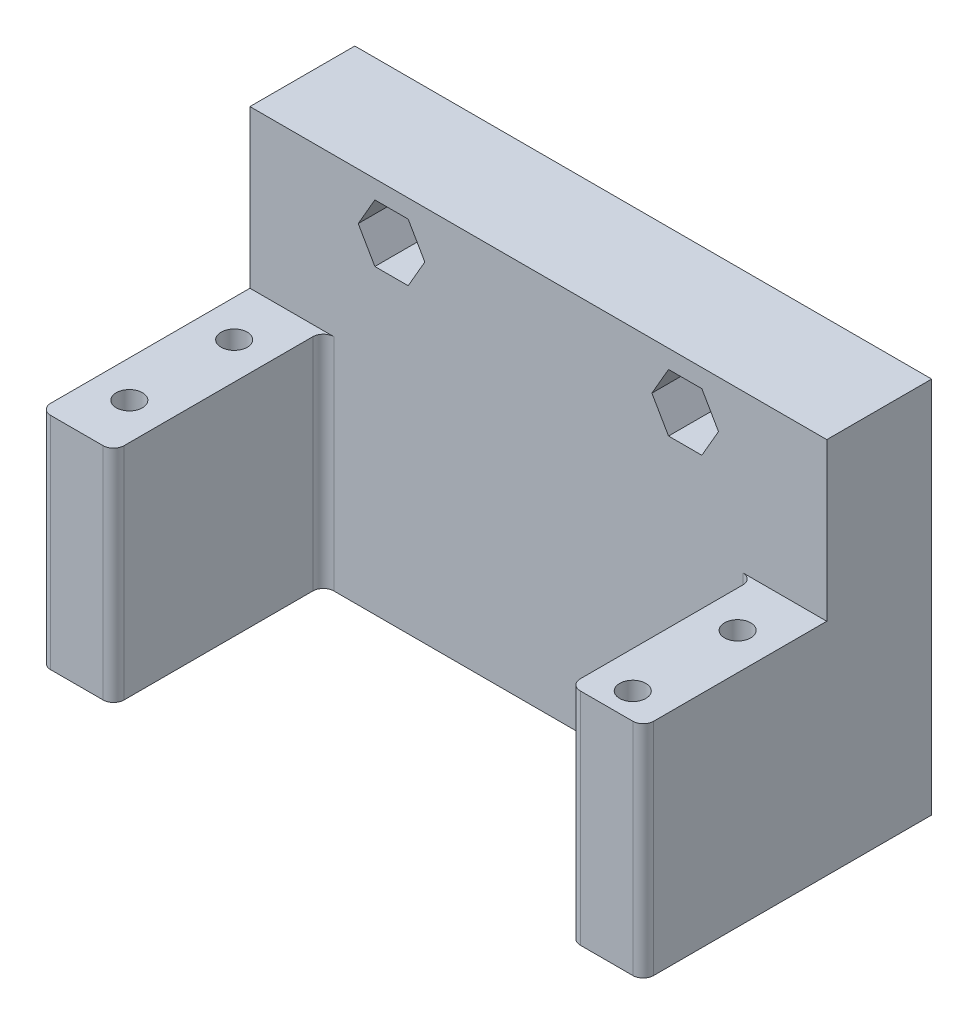
SolidWorks part; units mm, degrees
ref_plane "Front Plane" through (0, 0, 0) normal (0, 0, 1) x (1, 0, 0)
ref_plane "Top Plane" through (0, 0, 0) normal (0, 1, 0) x (1, 0, 0)
ref_plane "Right Plane" through (0, 0, 0) normal (1, 0, 0) x (0, 0, -1)
sketch "Sketch1" plane through (0, 0, 0) normal (0, 0, 1) x (1, 0, 0)
  line L1 (0, 0) -> (55, 0)
  line L2 (0, 0) -> (0, -36)
  line L3 (0, -36) -> (55, -36)
  line L4 (55, 0) -> (55, -36)
  circle A0 centre (13.5, -4.5) radius 2
  circle A1 centre (41.5, -4.5) radius 2
  dimension "D3" = 4.5
  dimension "D1" = 55
  dimension "D2" = 36
  dimension "D4" = 13.5
  dimension "D6" = 28
  dimension "D5" = 2
extrude "Boss-Extrude1" add sketch "Sketch1" along normal blind 10
sketch "Sketch2" plane through (0, -36, 0) normal (0, -1, 0) x (1, 0, 0)
  line L1 (0, 10) -> (7, 10)
  line L2 (0, 10) -> (0, 30)
  line L3 (0, 30) -> (7, 30)
  line L4 (7, 10) -> (7, 30)
  line L5 (55, 10) -> (48, 10)
  line L6 (55, 10) -> (55, 27.5)
  line L7 (55, 27.5) -> (48, 27.5)
  line L8 (48, 10) -> (48, 27.5)
  dimension "D1" = 41
  dimension "D2" = 7
  dimension "D3" = 20
extrude "Boss-Extrude2" add sketch "Sketch2" against normal blind 21
sketch "Sketch3" plane through (0, -15, 0) normal (0, 1, 0) x (1, 0, 0)
  line L0 (55, -10) -> (0, -10) construction
  line L1 (0, -30) -> (0, -10) construction
  circle A0 centre (3.5, -15) radius 1.25
  circle A1 centre (51.5, -15) radius 1.25
  circle A2 centre (51.5, -25) radius 1.25
  circle A3 centre (3.5, -25) radius 1.25
  dimension "D1" = 2
  dimension "D3" = 5
  dimension "D4" = 3.5
  dimension "D2" = 2
extrude "Cut-Extrude1" cut sketch "Sketch3" against normal blind 10
sketch "Sketch4" plane through (0, 0, 10) normal (0, 0, 1) x (1, 0, 0)
  line L1 (11.9123, -1.75) -> (10.3246, -4.5)
  line L2 (10.3246, -4.5) -> (11.9123, -7.25)
  line L3 (11.9123, -7.25) -> (15.0877, -7.25)
  line L4 (15.0877, -7.25) -> (16.6754, -4.5)
  line L5 (16.6754, -4.5) -> (15.0877, -1.75)
  line L6 (15.0877, -1.75) -> (11.9123, -1.75)
  circle A0 centre (13.5, -4.5) radius 2.75 construction
extrude "Cut-Extrude2" cut sketch "Sketch4" against normal blind 5.5
pattern_linear "LPattern1" count 2 spacing 28 along (1, 0, 0) of "Cut-Extrude2"
fillet "Fillet1" radius 1 6 edges at (48, -25.5, 27.5) (55, -25.5, 27.5) (7, -25.5, 30) (0, -25.5, 30) (48, -25.5, 10) (7, -25.5, 10)
sketch "Sketch5" plane through (0, 0, 0) normal (0, 1, 0) x (1, 0, 0)
  line L0 (27.5, 0) -> (27.5, -20)
  line L1 (55, 0) -> (0, 0) construction
  line L2 (27.5, -20) -> (37.5, -20)
  line L3 (27.5, 0) -> (27.5, 13.5)
  line L4 (27.5, 13.5) -> (37.5, -20)
